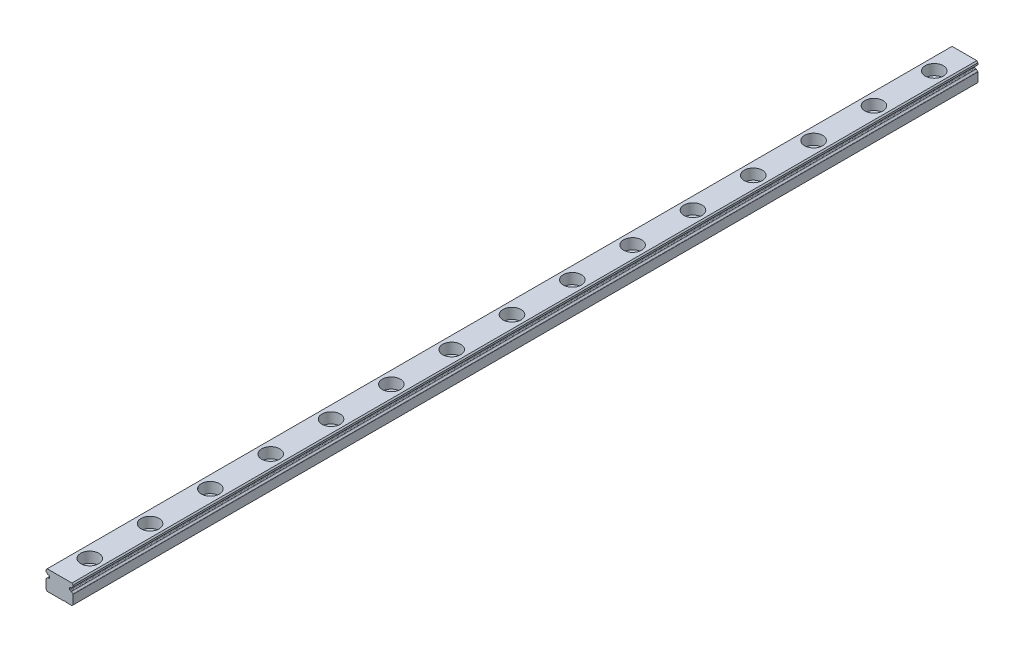
SolidWorks part; units mm, degrees
ref_plane "Front Plane" through (0, 0, 0) normal (0, 0, 1) x (1, 0, 0)
ref_plane "Top Plane" through (0, 0, 0) normal (0, 1, 0) x (1, 0, 0)
ref_plane "Right Plane" through (0, 0, 0) normal (1, 0, 0) x (0, 0, -1)
sketch "Sketch1" plane through (0, 0, 0) normal (0, 0, 1) x (1, 0, 0)
  line L0 (-4.5, 0) -> (4.5, 0) construction
  line L1 (0, -3.25) -> (0, 3.25) construction
  line L2 (0, 3.25) -> (0, -3.25) construction
  line L3 (-3, 3.25) -> (3, 3.25) construction
  line L4 (-1.75, -0.25) -> (1.75, -0.25) construction
  point P0 (0, -0.25)
  point P3 (-4.5, -3.25)
  point P4 (0, 0)
  point P8 (0, 0)
  point P11 (0, 3.25)
  point P15 (0, 3.25)
  point P17 (0, -0.25)
  point P18 (4.5, 3.25)
  point P20 (-4.5, 3.25)
  dimension "Rail Width" = 9
  dimension "Rail Height" = 6.5
  dimension "Mounting Hole Depth" = 3
  dimension "Mounting Hole Counterbore Diameter" = 6
  dimension "Mounting Hole Diameter" = 3.5
sketch "Sketch2" plane through (0, 0, 0) normal (1, 0, 0) x (0, 0, -1)
  line L0 (150, 0) -> (-150, 0) construction
  line L1 (-9.5, 3.25) -> (9.5, 3.25) construction
  line L3 (0, 3.25) -> (0, 0) construction
  point P0 (-140, 0)
  point P4 (0, 0)
  point P5 (-120, 0)
  point P6 (-130, 0)
  point P9 (-140, 3.25)
  point P10 (0, 3.25)
  point P11 (150, 3.25)
  point P13 (-150, 3.25)
  point P14 (130, 0)
  point P17 (-150, -3.25)
  dimension "Rail Length" = 300
  dimension "Mounting Hole Center to Edge" = 10
  dimension "Mounting Hole Center to Center" = 20
  dimension "Number of Mounting Holes" = 19
  dimension "Break Line" = 10
sketch "Sketch3" plane through (0, 0, 0) normal (0, 0, 1) x (1, 0, 0)
  point P0 (0, 3.25)
  line B0 (-4.5, 0.1917) -> (-4.5, -2.85)
  line B1 (-4.5, -2.85) -> (-4.1, -3.25)
  line B2 (-4.1, -3.25) -> (1.4, -3.25)
  line B3 (2.2, -3.25) -> (4.1, -3.25)
  line B4 (4.1, -3.25) -> (4.5, -2.85)
  line B5 (4.5, -2.85) -> (4.5, 0.1917)
  line B6 (3.8235, 0.8135) -> (3.4826, 0.8434)
  line B7 (3.3, 1.0426) -> (3.3, 1.4574)
  line B8 (3.4826, 1.6566) -> (3.8235, 1.6865)
  line B9 (4.5, 2.3083) -> (4.5, 2.85)
  line B10 (4.5, 2.85) -> (4.1, 3.25)
  line B11 (4.1, 3.25) -> (-4.1, 3.25)
  line B12 (-4.1, 3.25) -> (-4.5, 2.85)
  line B13 (-4.5, 2.85) -> (-4.5, 2.3083)
  line B14 (-3.8235, 1.6865) -> (-3.4826, 1.6566)
  line B15 (-3.3, 1.4574) -> (-3.3, 1.0426)
  line B16 (-3.4826, 0.8434) -> (-3.8235, 0.8135)
  arc B17 (2.2, -3.25) -> (1.4, -3.25) centre (1.8, -3.55) ccw
  arc B18 (4.5, 0.1917) -> (4.4087, 0.3297) centre (4.35, 0.1917) ccw
  arc B19 (3.9395, 0.7405) -> (4.4087, 0.3297) centre (4.8, 1.25) ccw
  arc B20 (3.9395, 0.7405) -> (3.8235, 0.8135) centre (3.8104, 0.6641) ccw
  arc B21 (3.3, 1.0426) -> (3.4826, 0.8434) centre (3.5, 1.0426) ccw
  arc B22 (3.4826, 1.6566) -> (3.3, 1.4574) centre (3.5, 1.4574) ccw
  arc B23 (3.8235, 1.6865) -> (3.9395, 1.7595) centre (3.8104, 1.8359) ccw
  arc B24 (4.4087, 2.1703) -> (3.9395, 1.7595) centre (4.8, 1.25) ccw
  arc B25 (4.4087, 2.1703) -> (4.5, 2.3083) centre (4.35, 2.3083) ccw
  arc B26 (-4.5, 2.3083) -> (-4.4087, 2.1703) centre (-4.35, 2.3083) ccw
  arc B27 (-3.9395, 1.7595) -> (-4.4087, 2.1703) centre (-4.8, 1.25) ccw
  arc B28 (-3.9395, 1.7595) -> (-3.8235, 1.6865) centre (-3.8104, 1.8359) ccw
  arc B29 (-3.3, 1.4574) -> (-3.4826, 1.6566) centre (-3.5, 1.4574) ccw
  arc B30 (-3.4826, 0.8434) -> (-3.3, 1.0426) centre (-3.5, 1.0426) ccw
  arc B31 (-3.8235, 0.8135) -> (-3.9395, 0.7405) centre (-3.8104, 0.6641) ccw
  arc B32 (-4.4087, 0.3297) -> (-3.9395, 0.7405) centre (-4.8, 1.25) ccw
  arc B33 (-4.4087, 0.3297) -> (-4.5, 0.1917) centre (-4.35, 0.1917) ccw
sketch_block_instance "9mm Block-1"
sketch_block "9mm Block"
extrude "Boss-Extrude1" add sketch "Sketch3" against normal up to vertex (150 mm away) from vertex at 150 starting at point (0, 0, 150)
ref_plane "Plane1" through (0, 0, 140) normal (0, 0, 1) x (1, 0, 0)
sketch "Sketch4" plane through (0, 0, 140) normal (0, 0, 1) x (1, 0, 0)
  line L0 (0, 3.25) -> (0, -3.25)
  line L1 (0, -3.25) -> (-1.75, -3.25)
  line L3 (-1.75, -3.25) -> (-1.75, -0.25)
  line L4 (-1.75, -0.25) -> (-3, -0.25)
  line L5 (-3, -0.25) -> (-3, 3.25)
  line L6 (-3, 3.25) -> (0, 3.25)
  point P6 (-1.75, -0.25)
revolve "Cut-Revolve1" cut sketch "Sketch4" angle 360 about L0
sketch "Sketch6" plane through (0, 0, 0) normal (1, 0, 0) x (0, 0, -1)
  line L0 (-137, -0.25) -> (-143, -0.25) construction
  line L5 (-137, -0.25) -> (-143, -0.25)
  line L17 (-141.75, -0.25) -> (-141.75, -3.25) construction
  line L18 (-138.25, -3.25) -> (-138.25, -0.25) construction
  line L32 (-137, -0.25) -> (-137, 3.25) construction
  line L33 (-143, 3.25) -> (-143, -0.25) construction
  line L34 (-141.75, -0.25) -> (-141.75, -3.25)
  line L35 (-138.25, -3.25) -> (-138.25, -0.25)
  line L36 (-137, -0.25) -> (-137, 3.25)
  line L37 (-143, 3.25) -> (-143, -0.25)
  line L38 (0, 3.25) -> (0, -3.25) construction
  line L40 (143, 3.25) -> (143, -0.25)
  line L41 (137, -0.25) -> (137, 3.25)
  line L42 (138.25, -3.25) -> (138.25, -0.25)
  line L43 (141.75, -0.25) -> (141.75, -3.25)
  line L44 (137, -0.25) -> (143, -0.25)
sketch "Sketch7" plane through (0, 0, 0) normal (0, 0, 1) x (1, 0, 0)
  line L0 (3, -0.25) -> (3, 3.25) construction
  line L1 (-3, 3.25) -> (-3, -0.25) construction
  line L2 (3, -0.25) -> (3, 3.25)
  line L3 (-3, 3.25) -> (-3, -0.25)
  line L4 (1.75, -3.0525) -> (1.75, -0.25) construction
  line L11 (1.75, -3.0525) -> (1.75, -0.25)
  line L18 (-1.75, -0.25) -> (-1.75, -3.25) construction
  line L32 (3, -0.25) -> (-3, -0.25) construction
  line L34 (-1.75, -0.25) -> (-1.75, -3.25)
  line L37 (3, -0.25) -> (-3, -0.25)
pattern_linear "LPattern1" count 15 spacing 20 along (0, 0, -1) of "Cut-Revolve1"
equation "\"D3@LPattern1\"=\"Mounting Hole Center to Center@Sketch2\""
equation "\"Break Line@Sketch2\"=\"Mounting Hole Center to Center@Sketch2\"/2"
